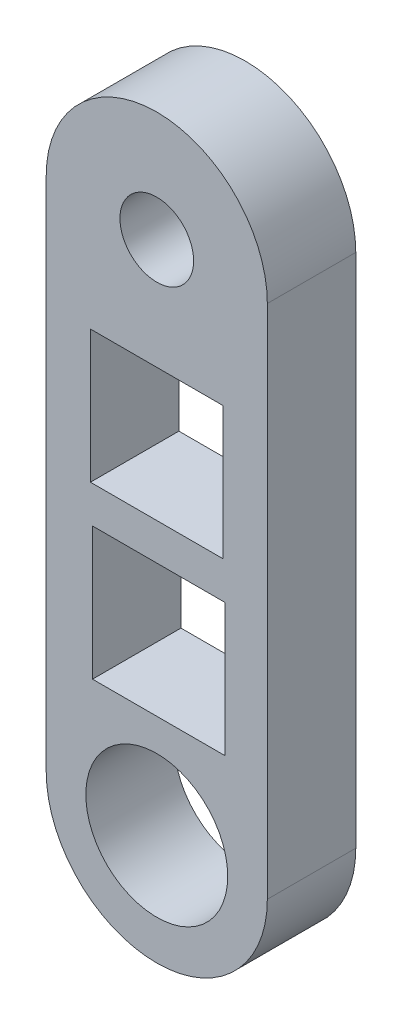
SolidWorks part; units mm, degrees
ref_plane "Front Plane" through (0, 0, 0) normal (0, 0, 1) x (1, 0, 0)
ref_plane "Top Plane" through (0, 0, 0) normal (0, 1, 0) x (1, 0, 0)
ref_plane "Right Plane" through (0, 0, 0) normal (1, 0, 0) x (0, 0, -1)
sketch "Sketch1" plane through (0, 0, 0) normal (0, 0, 1) x (1, 0, 0)
  line L0 (0, 45) -> (0, -25) construction
  line L1 (0, -55) -> (0, 55) construction
  line L2 (15, 45) -> (15, -25)
  line L3 (-15, 45) -> (-15, -25)
  line L4 (16.5, 0) -> (-16.5, 0) construction
  line L10 (-9, 30) -> (9, 30)
  line L11 (-9, 30) -> (-9, 12)
  line L12 (-9, 12) -> (9, 12)
  line L13 (9, 30) -> (9, 12)
  line L14 (-8.7177, 7) -> (9.2823, 7)
  line L15 (-8.7177, 7) -> (-8.7177, -11)
  line L16 (-8.7177, -11) -> (9.2823, -11)
  line L17 (9.2823, 7) -> (9.2823, -11)
  arc A0 (15, 45) -> (-15, 45) centre (0, 45) ccw
  arc A1 (-15, -25) -> (15, -25) centre (0, -25) ccw
  circle A3 centre (0, -25) radius 9.625
  circle A4 centre (0, 45) radius 5
  point P5 (0, 10)
  dimension "D3" = 15
  dimension "D14" = 19.25
  dimension "D4" = 10
  dimension "D1" = 70
  dimension "D2" = 45
  dimension "D8" = 18
  dimension "D9" = 9
  dimension "18" = 18
  dimension "D10" = 15
  dimension "D11" = 18
  dimension "D12" = 18
  dimension "D13" = 5
extrude "Boss-Extrude1" add sketch "Sketch1" along normal blind 12
